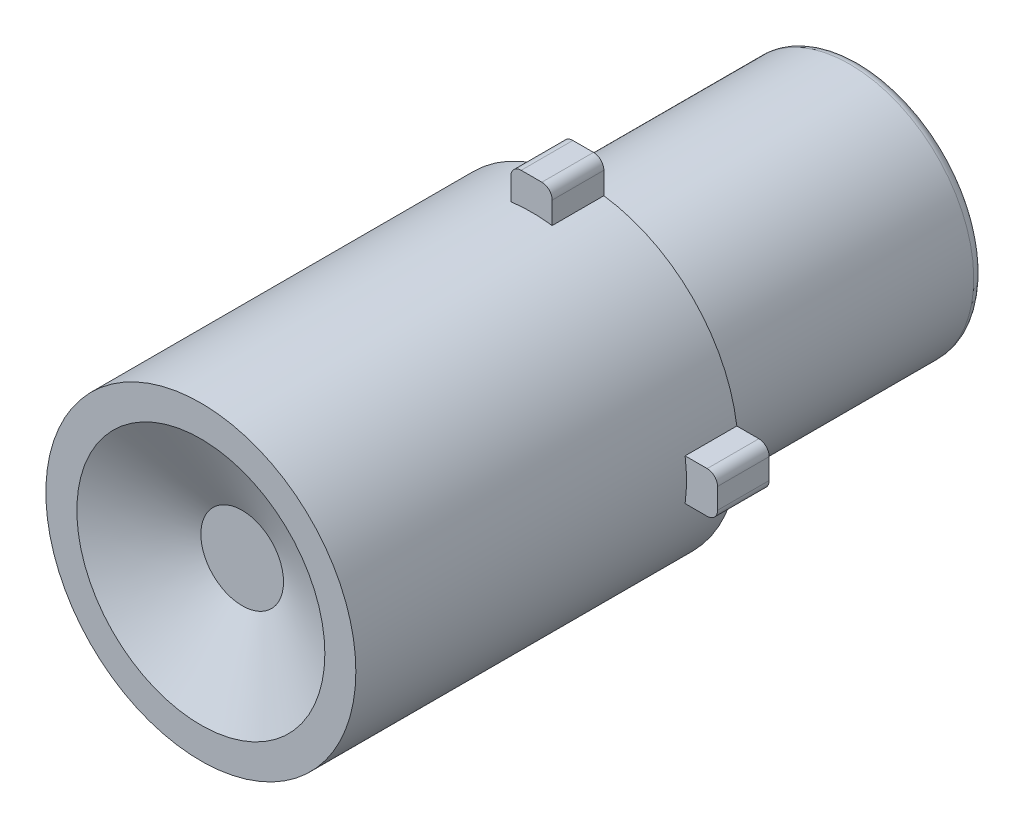
SolidWorks part; units mm, degrees
ref_plane "Ön Düzlem" through (0, 0, 0) normal (0, 0, 1) x (1, 0, 0)
ref_plane "Üst Düzlem" through (0, 0, 0) normal (0, 1, 0) x (1, 0, 0)
ref_plane "Sağ Düzlem" through (0, 0, 0) normal (1, 0, 0) x (0, 0, -1)
sketch "Sketch1" plane through (0, 0, 0) normal (0, 0, 1) x (1, 0, 0)
  circle A0 centre (0, 0) radius 3.75
  dimension "D1" = 7.5
extrude "Boss-Extrude1" add sketch "Sketch1" along normal blind 10
sketch "Sketch3" plane through (0, 0, 0) normal (0, 1, 0) x (1, 0, 0)
  line L0 (-3, -10) -> (0, -10)
  line L1 (-3.75, -10) -> (3.75, -10) construction
  line L2 (0, -10) -> (0, -9)
  line L3 (0, -9) -> (-1, -9)
  line L4 (-1, -9) -> (-3, -10)
  dimension "D1" = 1
  dimension "D2" = 3
  dimension "D3" = 1
revolve "Cut-Revolve1" cut sketch "Sketch3" angle 360 about L2
sketch "Sketch4" plane through (0, 0, 0) normal (0, 0, -1) x (-1, 0, 0)
  line L0 (0.5, 3.5) -> (-0.5, 3.5)
  line L1 (-3.5, 0.5) -> (-4.5, 0.5)
  line L2 (-3.5, 0.5) -> (-3.5, -0.5)
  line L3 (-3.5, -0.5) -> (-4.5, -0.5)
  line L4 (-4.5, 0.5) -> (-4.5, -0.5)
  line L5 (0.5, 3.5) -> (0.5, 4.5)
  line L6 (0.5, 4.5) -> (-0.5, 4.5)
  line L7 (-0.5, 3.5) -> (-0.5, 4.5)
  line L8 (3.5, -0.5) -> (3.5, 0.5)
  line L9 (3.5, -0.5) -> (4.5, -0.5)
  line L10 (4.5, -0.5) -> (4.5, 0.5)
  line L11 (3.5, 0.5) -> (4.5, 0.5)
  line L12 (-0.5, -3.5) -> (0.5, -3.5)
  line L13 (-0.5, -3.5) -> (-0.5, -4.5)
  line L14 (-0.5, -4.5) -> (0.5, -4.5)
  line L15 (0.5, -3.5) -> (0.5, -4.5)
  point P4 (-3.5, 0)
  point P21 (0, 0)
  dimension "D1" = 1
  dimension "D2" = 1
  dimension "D3" = 3.5
  dimension "D4" = 4
extrude "Boss-Extrude2" add sketch "Sketch4" against normal blind 2
sketch "Sketch5" plane through (0, 0, 0) normal (1, 0, 0) x (0, 0, -1)
  line L0 (0, -3.7165) -> (0, -0.5) construction
  line L1 (2.3445, 6.7666) -> (-0.75, 6.7666)
  line L2 (2.3445, 6.7666) -> (2.3445, -6.4778)
  line L3 (2.3445, -6.4778) -> (-0.75, -6.4778)
  line L4 (-0.75, 6.7666) -> (-0.75, -6.4778)
  dimension "D1" = 0.75
extrude "Cut-Extrude1" cut sketch "Sketch5" against normal blind 6.5 and the other way blind 6.5
sketch "Sketch6" plane through (0, 0, 0.75) normal (0, 0, -1) x (-1, 0, 0)
  circle A0 centre (0, 0) radius 3
  dimension "D1" = 6
extrude "Boss-Extrude3" add sketch "Sketch6" along normal blind 6.7
sketch "Sketch7" plane through (0, 0, -5.95) normal (0, 0, -1) x (-1, 0, 0)
  circle A0 centre (0, 0) radius 2.5
  dimension "D1" = 5
extrude "Cut-Extrude2" cut sketch "Sketch7" against normal blind 1.25
fillet "Fillet2" radius 0.25 1 edges at (0, 3, -5.95)
fillet "Fillet3" radius 0.25 8 edges at (-4.5, 0.5, 1.375) (-4.5, -0.5, 1.375) (-0.5, -4.5, 1.375) (0.5, -4.5, 1.375) (4.5, -0.5, 1.375) (4.5, 0.5, 1.375) (-0.5, 4.5, 1.375) (0.5, 4.5, 1.375)
